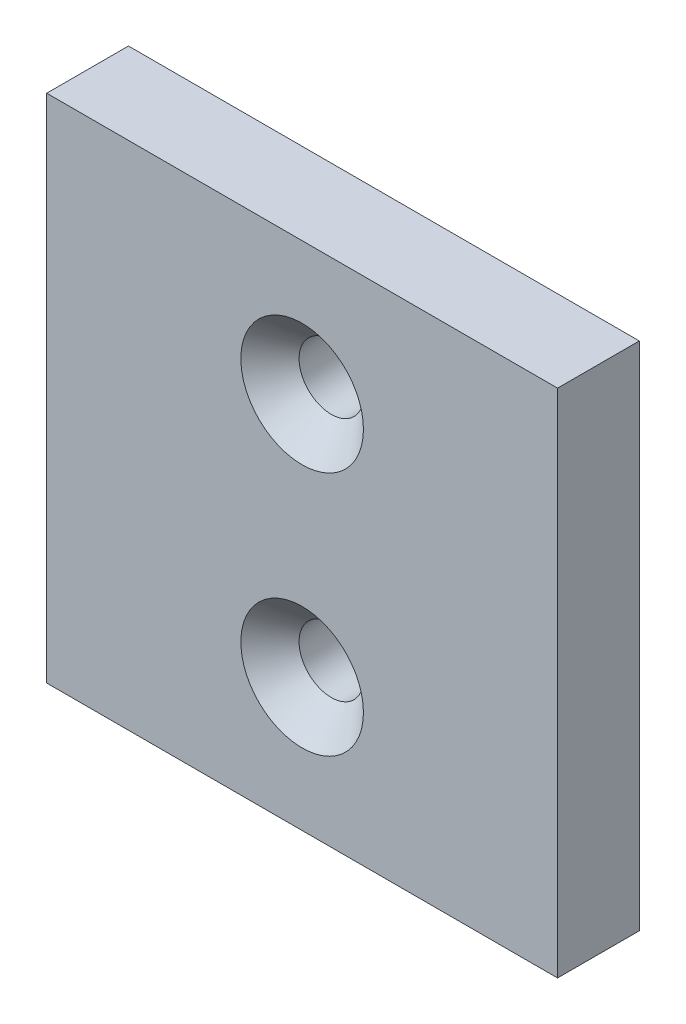
SolidWorks part; units mm, degrees
material "Chrome Stainless Steel"
ref_plane "Front Plane" through (0, 0, 0) normal (0, 0, 1) x (1, 0, 0)
ref_plane "Top Plane" through (0, 0, 0) normal (0, 1, 0) x (1, 0, 0)
ref_plane "Right Plane" through (0, 0, 0) normal (1, 0, 0) x (0, 0, -1)
sketch "Sketch1" plane through (0, 0, 0) normal (0, 0, 1) x (1, 0, 0)
  line L1 (-25, -25) -> (25, -25)
  line L2 (-25, -25) -> (-25, 25)
  line L3 (-25, 25) -> (25, 25)
  line L4 (25, -25) -> (25, 25)
  line L5 (-25, -25) -> (25, 25) construction
  line L6 (-25, 25) -> (25, -25) construction
  point P0 (0, 0)
  dimension "D1" = 50
  dimension "D2" = 50
extrude "Boss-Extrude1" add sketch "Sketch1" along normal blind 8
sketch "Sketch2" plane through (0, 0, 8) normal (0, 0, 1) x (1, 0, 0)
  line L0 (25, 25) -> (-25, 25) construction
  line L1 (-25, 25) -> (-25, -25) construction
  point P0 (0, 12)
  point P1 (0, -12)
  dimension "D1" = 24
  dimension "D2" = 13
  dimension "D3" = 25
hole_wizard "Hole1" positions "3DSketch1" profile "Sketch3" legacy
sketch3d "3DSketch1"
  point P0 (0, 12, 8)
  point P3 (0, -12, 8)
sketch "Sketch3" plane through (0, 12, 8) normal (1, 0, 0) x (0, -1, 0)
  line L0 (0, 0) -> (0, 8)
  line L1 (0, 8) -> (3.15, 8)
  line L2 (3.15, 8) -> (3.15, 2.85)
  line L3 (3.15, 2.85) -> (6, 0)
  line L4 (6, 0) -> (0, 0)
  line L5 (0, -6.4453) -> (0, 115.525) construction
  line L6 (-3.15, 2.85) -> (-6, 0) construction
  dimension "Diameter" = 6.3
  dimension "Depth" = 8
  dimension "C-Sink Angle" = 90
  dimension "C-Sink Diameter" = 12
